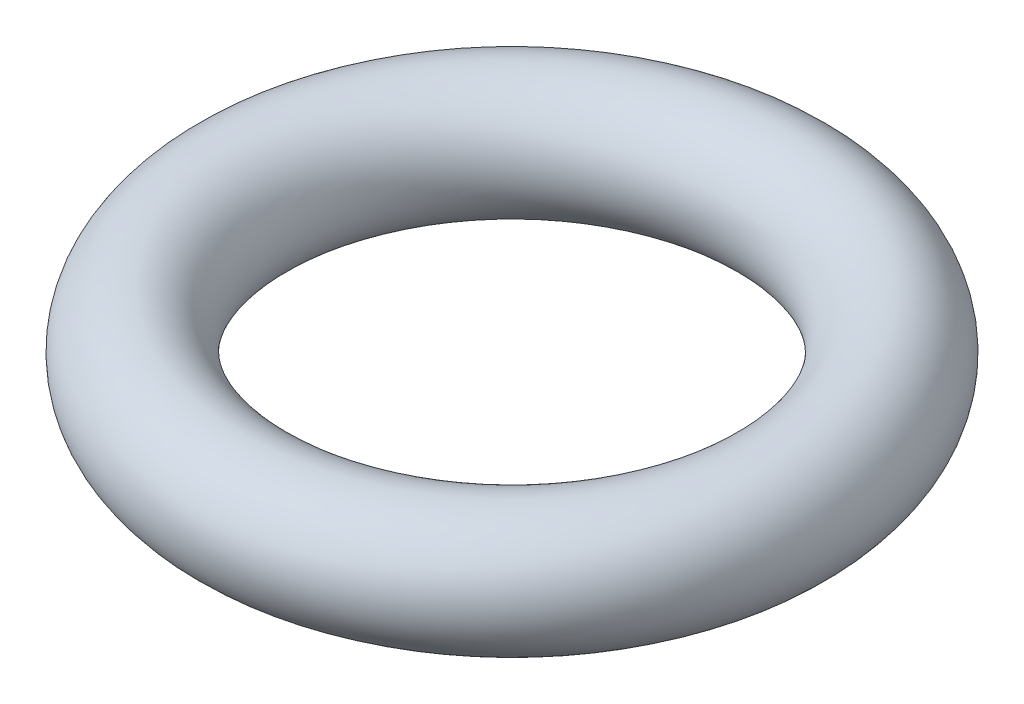
SolidWorks part; units mm, degrees
material "橡胶"
ref_plane "前视基准面" through (0, 0, 0) normal (0, 0, 1) x (1, 0, 0)
ref_plane "上视基准面" through (0, 0, 0) normal (0, 1, 0) x (1, 0, 0)
ref_plane "右视基准面" through (0, 0, 0) normal (1, 0, 0) x (0, 0, -1)
sketch "草图1" plane through (0, 0, 0) normal (0, 0, 1) x (1, 0, 0)
  line L0 (0, 0) -> (-5.5, 0) construction
  line L1 (0, 0) -> (0, 5.5) construction
  circle A1 centre (-5.5, 0) radius 1.25
  dimension "D1" = 2.5
  dimension "D2" = 5.5
revolve "旋转1" add sketch "草图1" angle 360 about L1
sketch "草图3" plane through (0, 0, 0) normal (0, 1, 0) x (1, 0, 0)
  circle A0 centre (0, 0) radius 3.5
  dimension "D1" = 7
